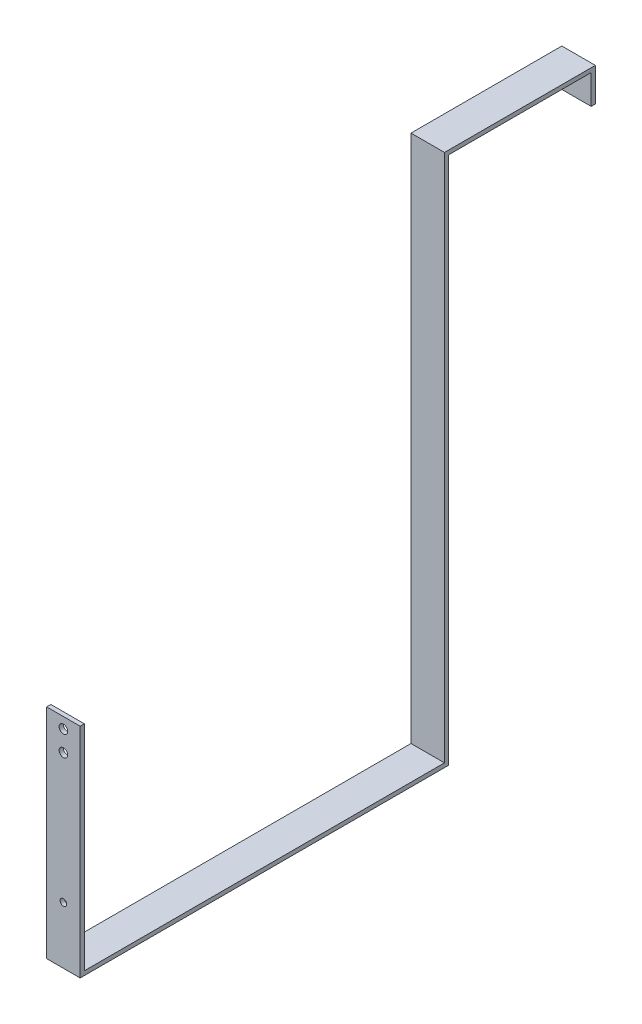
SolidWorks part; units mm, degrees
ref_plane "Alzado" through (0, 0, 0) normal (0, 0, 1) x (1, 0, 0)
ref_plane "Planta" through (0, 0, 0) normal (0, 1, 0) x (1, 0, 0)
ref_plane "Vista lateral" through (0, 0, 0) normal (1, 0, 0) x (0, 0, -1)
sketch "Croquis1" plane through (0, 0, 0) normal (0, 0, 1) x (1, 0, 0)
  line L1 (-25.4, -3.155) -> (25.4, -3.155)
  line L2 (-25.4, -3.155) -> (-25.4, 3.155)
  line L3 (-25.4, 3.155) -> (25.4, 3.155)
  line L4 (25.4, -3.155) -> (25.4, 3.155)
  line L5 (-25.4, -3.155) -> (25.4, 3.155) construction
  line L6 (-25.4, 3.155) -> (25.4, -3.155) construction
  point P0 (0, 0)
  dimension "D1" = 6.31
  dimension "D2" = 50.8
extrude "Saliente-Extruir1" add sketch "Croquis1" along normal blind 228.75
sketch "Croquis2" plane through (0, -3.155, 0) normal (0, -1, 0) x (1, 0, 0)
  line L0 (-25.4, 228.75) -> (25.4, 228.75)
  line L1 (25.4, 228.75) -> (25.4, 222.44)
  line L2 (25.4, 228.75) -> (25.4, 0) construction
  line L3 (25.4, 222.44) -> (-25.4, 222.44)
  line L4 (-25.4, 228.75) -> (-25.4, 0) construction
  line L5 (-25.4, 222.44) -> (-25.4, 228.75)
  dimension "D1" = 6.31
extrude "Saliente-Extruir2" add sketch "Croquis2" along normal blind 801.67
sketch "Croquis3" plane through (0, 0, 228.75) normal (0, 0, 1) x (1, 0, 0)
  line L0 (-25.4, -804.825) -> (25.4, -804.825)
  line L1 (25.4, -804.825) -> (25.4, -798.515)
  line L2 (25.4, -804.825) -> (25.4, 3.155) construction
  line L3 (25.4, -798.515) -> (-25.4, -798.515)
  line L4 (-25.4, 3.155) -> (-25.4, -804.825) construction
  line L5 (-25.4, -798.515) -> (-25.4, -804.825)
  dimension "D1" = 6.31
extrude "Saliente-Extruir3" add sketch "Croquis3" along normal blind 552.5
sketch "Croquis4" plane through (0, -798.515, 0) normal (0, 1, 0) x (1, 0, 0)
  line L0 (-25.4, -781.25) -> (25.4, -781.25)
  line L1 (25.4, -781.25) -> (25.4, -774.94)
  line L2 (25.4, -781.25) -> (25.4, -228.75) construction
  line L3 (25.4, -774.94) -> (-25.4, -774.94)
  line L4 (-25.4, -781.25) -> (-25.4, -228.75) construction
  line L5 (-25.4, -774.94) -> (-25.4, -781.25)
  dimension "D1" = 6.31
extrude "Saliente-Extruir4" add sketch "Croquis4" along normal blind 314.39
sketch "Croquis5" plane through (0, 0, 781.25) normal (0, 0, 1) x (1, 0, 0)
  line L0 (0, -383.4472) -> (0, -484.125) construction
  line L1 (-25.4, -484.125) -> (25.4, -484.125) construction
  line L2 (0, -383.4472) -> (0, -415.4472) construction
  line L3 (0, -415.4472) -> (21.1091, -415.4472) construction
  circle A0 centre (0, -383.4472) radius 6.35
  circle A1 centre (0, -415.4472) radius 6.35
sketch "Croquis6" plane through (0, -484.125, 0) normal (0, 1, 0) x (1, 0, 0)
  line L0 (25.4, -781.25) -> (-25.4, -781.25)
  line L1 (-25.4, -781.25) -> (-25.4, -774.94)
  line L2 (-25.4, -774.94) -> (25.4, -774.94)
  line L3 (25.4, -774.94) -> (25.4, -781.25)
extrude "Saliente-Extruir5" add sketch "Croquis6" along normal blind 10
sketch "Croquis7" plane through (0, 3.155, 0) normal (0, 1, 0) x (1, 0, 0)
  line L0 (25.4, 0) -> (25.4, -6.31)
  line L1 (25.4, -228.75) -> (25.4, 0) construction
  line L2 (25.4, -6.31) -> (-25.4, -6.31)
  line L3 (-25.4, -228.75) -> (-25.4, 0) construction
  line L4 (-25.4, -6.31) -> (-25.4, 0)
  line L5 (-25.4, 0) -> (25.4, 0)
  dimension "D1" = 6.31
extrude "Saliente-Extruir6" add sketch "Croquis7" against normal blind 50.8
sketch "Croquis12" plane through (0, 0, 781.25) normal (0, 0, 1) x (1, 0, 0)
  line L0 (0, -474.125) -> (0, -490.625) construction
  line L1 (-25.4, -474.125) -> (25.4, -474.125) construction
  line L2 (0, -490.625) -> (0, -521.625) construction
  circle A0 centre (0, -521.625) radius 6.5
  circle A1 centre (0, -490.625) radius 6.5
  dimension "D3" = 13
  dimension "D4" = 13
  dimension "D1" = 16.5
  dimension "D2" = 31
extrude "Cortar-Extruir3" cut sketch "Croquis12" against normal blind 10
sketch "Croquis13" plane through (0, 0, 781.25) normal (0, 0, 1) x (1, 0, 0)
  line L0 (0, -804.825) -> (0, -711.425) construction
  line L1 (-25.4, -804.825) -> (25.4, -804.825) construction
  line L2 (0, -711.425) -> (0, -718.315) construction
  line L3 (0, -718.315) -> (0, -695.315) construction
  circle A0 centre (0, -711.425) radius 3.5 construction
  circle A1 centre (0, -695.315) radius 3.5 construction
  circle A2 centre (0, -718.315) radius 5
  dimension "D4" = 7
  dimension "D5" = 10
  dimension "D6" = 7
  dimension "D1" = 86.51
  dimension "D3" = 23
extrude "Cortar-Extruir4" cut sketch "Croquis13" against normal blind 35
